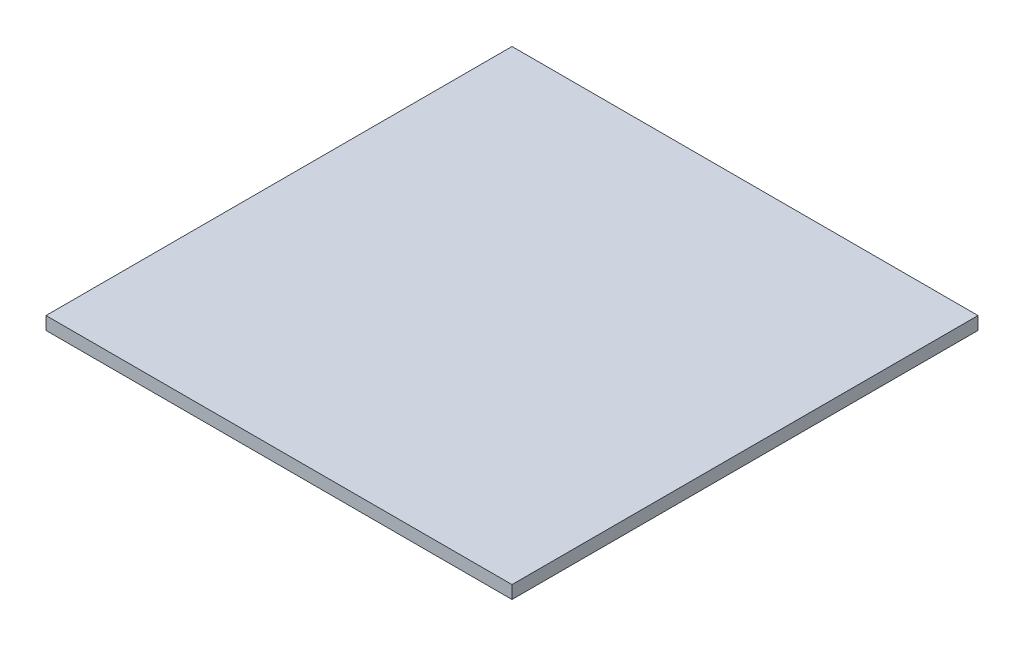
SolidWorks part; units mm, degrees
material "유리"
ref_plane "정면" through (0, 0, 0) normal (0, 0, 1) x (1, 0, 0)
ref_plane "윗면" through (0, 0, 0) normal (0, 1, 0) x (1, 0, 0)
ref_plane "우측면" through (0, 0, 0) normal (1, 0, 0) x (0, 0, -1)
sketch "스케치1" plane through (0, 0, 0) normal (0, 1, 0) x (1, 0, 0)
  line L1 (-54, -54) -> (54, -54)
  line L2 (-54, -54) -> (-54, 54)
  line L3 (-54, 54) -> (54, 54)
  line L4 (54, -54) -> (54, 54)
  line L5 (-54, -54) -> (54, 54) construction
  line L6 (-54, 54) -> (54, -54) construction
  point P0 (0, 0)
  dimension "D1" = 108
  dimension "D2" = 108
extrude "보스-돌출1" add sketch "스케치1" along normal blind 3
